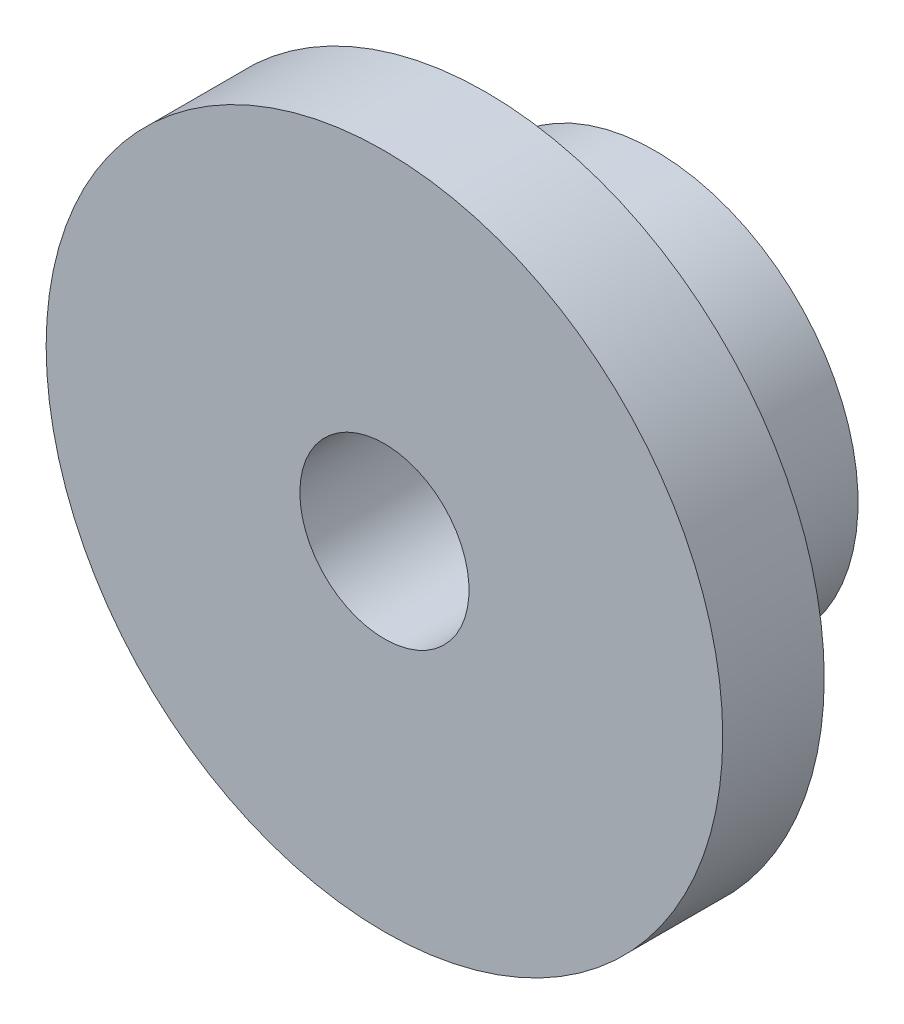
SolidWorks part; units mm, degrees
ref_plane "Front Plane" through (0, 0, 0) normal (0, 0, 1) x (1, 0, 0)
ref_plane "Top Plane" through (0, 0, 0) normal (0, 1, 0) x (1, 0, 0)
ref_plane "Right Plane" through (0, 0, 0) normal (1, 0, 0) x (0, 0, -1)
sketch "Sketch1" plane through (0, 0, 0) normal (0, 0, 1) x (1, 0, 0)
  circle A0 centre (0, 0) radius 10
  dimension "D1" = 20
extrude "Boss-Extrude1" add sketch "Sketch1" along normal blind 3
sketch "Sketch2" plane through (0, 0, 0) normal (0, 0, -1) x (-1, 0, 0)
  circle A0 centre (0, 0) radius 6
  dimension "D1" = 12
extrude "Boss-Extrude2" add sketch "Sketch2" along normal blind 5
hole_wizard "Tap Drill for M6 Tap1" positions "Sketch3" profile "Sketch4" hole size "M6" standard "ISO" end condition through all
sketch "Sketch3" plane through (0, 0, -5) normal (0, 0, -1) x (-1, 0, 0)
  point P0 (0, 0)
sketch "Sketch4" plane through (0, 0, -5) normal (1, 0, 0) x (0, 1, 0)
  line L0 (0, 0) -> (0, 8)
  line L1 (0, 8) -> (2.5, 8)
  line L2 (2.5, 8) -> (2.5, 0)
  line L5 (2.5, 0) -> (0, 0)
  line L11 (0, -6.35) -> (0, 107.95) construction
  dimension "Thru Hole Dia." = 5
  dimension "Thru Hole Depth" = 8
